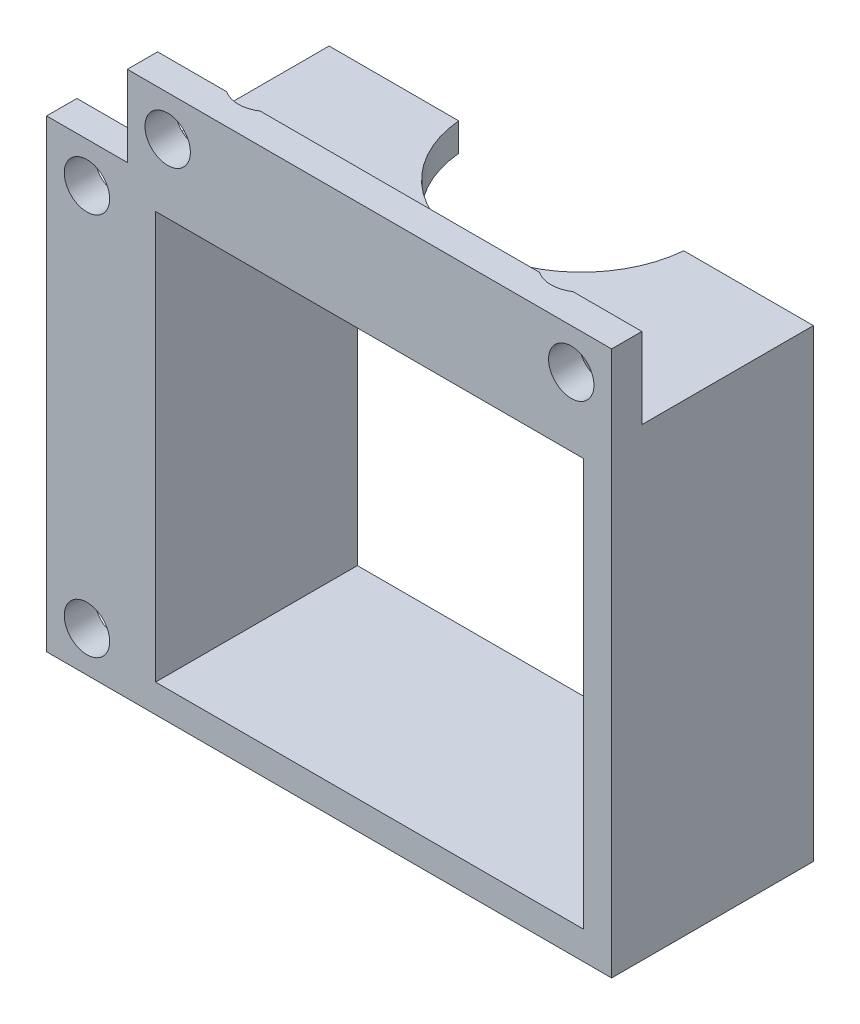
SolidWorks part; units mm, degrees
material "ABS"
ref_plane "前视基准面" through (0, 0, 0) normal (0, 0, 1) x (1, 0, 0)
ref_plane "上视基准面" through (0, 0, 0) normal (0, 1, 0) x (1, 0, 0)
ref_plane "右视基准面" through (0, 0, 0) normal (1, 0, 0) x (0, 0, -1)
sketch "Sketch1" plane through (0, 0, 0) normal (0, 0, 1) x (1, 0, 0)
  line L0 (-28.1067, -26.5) -> (19.8933, -26.5)
  line L5 (19.8933, -26.5) -> (19.8933, -72.5)
  line L6 (-28.1067, -72.5) -> (19.8933, -72.5)
  line L7 (-28.1067, -26.5) -> (-28.1067, -72.5)
  line L8 (-25.3067, -29.3) -> (17.0933, -29.3)
  line L9 (17.0933, -29.3) -> (17.0933, -69.7)
  line L10 (-25.3067, -69.7) -> (17.0933, -69.7)
  line L11 (-25.3067, -29.3) -> (-25.3067, -69.7)
extrude "Boss-Extrude1" add sketch "Sketch1" against normal blind 20
sketch "Sketch3" plane through (0, -26.5, 0) normal (0, 1, 0) x (1, 0, 0)
  circle A0 centre (-4.1067, 21) radius 11.2
  dimension "D1" = 22.4
extrude "Cut-Extrude1" cut sketch "Sketch3" against normal up to next
sketch "Sketch5" plane through (0, -26.5, 0) normal (0, 1, 0) x (1, 0, 0)
  circle A8 centre (11.3933, 5.5) radius 1.7
  circle A9 centre (-19.6067, 5.5) radius 1.7
  dimension "D1" = 3.4
extrude "Cut-Extrude2" cut sketch "Sketch5" against normal up to next
sketch "Sketch6" plane through (0, 0, 0) normal (0, 0, 1) x (1, 0, 0)
  line L5 (19.8933, -26.5) -> (-28.1067, -26.5) construction
  line L11 (-28.1067, -26.5) -> (-28.1067, -72.5) construction
  line B0 (-28.1067, -72.5) -> (-28.1067, -26.5)
  line B1 (-28.1067, -72.5) -> (-36.1067, -72.5)
  line B2 (-36.1067, -72.5) -> (-36.1067, -26.5)
  line B3 (-28.1067, -26.5) -> (-36.1067, -26.5)
  line B4 (-36.1067, -49.5) -> (-28.1067, -49.5) construction
  line B5 (-32.1067, -72.5) -> (-32.1067, -26.5) construction
  circle B6 centre (-32.1067, -68.5) radius 2.25
  circle B7 centre (-32.1067, -30.5) radius 2.25
  line B8 (19.8933, -18.5) -> (-28.1067, -18.5)
  line B9 (19.8933, -18.5) -> (19.8933, -26.5)
  line B10 (19.8933, -26.5) -> (-28.1067, -26.5)
  line B11 (-28.1067, -18.5) -> (-28.1067, -26.5)
  line B12 (-4.1067, -26.5) -> (-4.1067, -18.5) construction
  line B13 (19.8933, -22.5) -> (-28.1067, -22.5) construction
  circle B14 centre (15.8933, -22.5) radius 2.25
  circle B15 centre (-24.1067, -22.5) radius 2.25
sketch_block_instance "Block1-3"
sketch_block "Block1" parameters "D3"=4.5, "D1"=8, "D2"=22, "D4"=19, "D5"=19
sketch_block_instance "Block2-1"
sketch_block "Block2" parameters "D2"=4.5, "D1"=8, "D3"=20, "D4"=20, "D5"=48
extrude "Boss-Extrude2" add sketch "Sketch6" against normal blind 3
sketch "Sketch7" plane through (0, -18.5, 0) normal (0, 1, 0) x (1, 0, 0)
  circle A0 centre (11.3933, 5.5) radius 3
  circle A1 centre (-19.6067, 5.5) radius 3
  dimension "D1" = 6
extrude "Cut-Extrude3" cut sketch "Sketch7" against normal up to surface (8 mm away) up to face at (-4.1067, -26.5, -12.6333)
